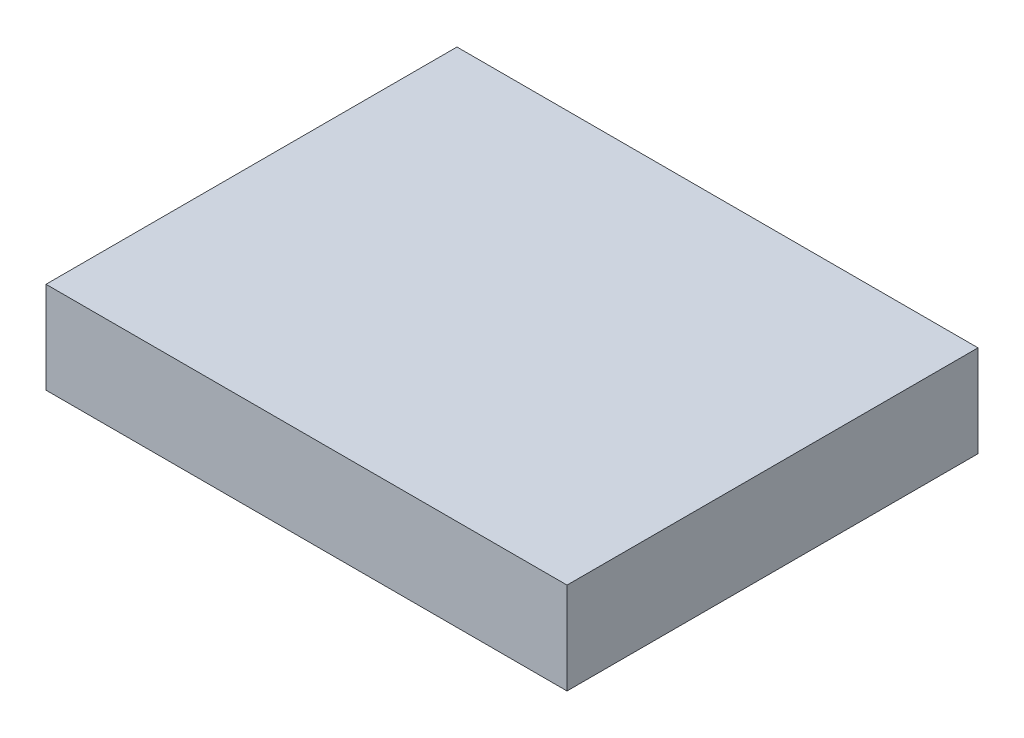
SolidWorks part; units mm, degrees
ref_plane "Front Plane" through (0, 0, 0) normal (0, 0, 1) x (1, 0, 0)
ref_plane "Top Plane" through (0, 0, 0) normal (0, 1, 0) x (1, 0, 0)
ref_plane "Right Plane" through (0, 0, 0) normal (1, 0, 0) x (0, 0, -1)
sketch "Sketch1" plane through (0, 0, 0) normal (0, 1, 0) x (1, 0, 0)
  line L1 (0, 0) -> (71, 0)
  line L2 (0, 0) -> (0, 56)
  line L3 (0, 56) -> (71, 56)
  line L4 (71, 0) -> (71, 56)
  dimension "D1" = 71
  dimension "D2" = 56
extrude "Boss-Extrude1" add sketch "Sketch1" along normal blind 12.5
